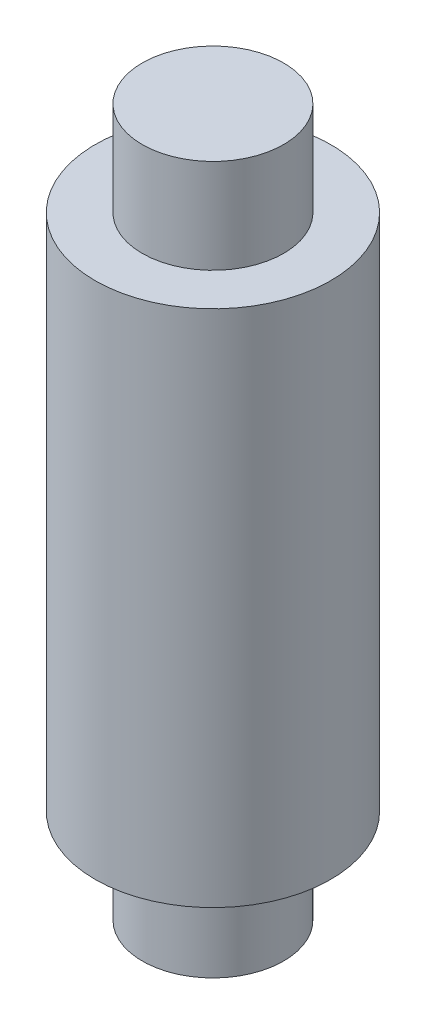
SolidWorks part; units mm, degrees
ref_plane "Спереди" through (0, 0, 0) normal (0, 0, 1) x (1, 0, 0)
ref_plane "Сверху" through (0, 0, 0) normal (0, 1, 0) x (1, 0, 0)
ref_plane "Справа" through (0, 0, 0) normal (1, 0, 0) x (0, 0, -1)
sketch "Эскиз1" plane through (0, 0, 0) normal (0, 1, 0) x (1, 0, 0)
  circle A0 centre (0, 0) radius 2.5
  dimension "D1" = 5
extrude "Бобышка-Вытянуть1" add sketch "Эскиз1" along normal blind 11
sketch "Эскиз2" plane through (0, 11, 0) normal (0, 1, 0) x (1, 0, 0)
  circle A0 centre (0, 0) radius 1.5
  dimension "D1" = 3
extrude "Бобышка-Вытянуть2" add sketch "Эскиз2" along normal blind 2
sketch "Эскиз4" plane through (0, 0, 0) normal (0, -1, 0) x (1, 0, 0)
  circle A0 centre (0, 0) radius 1.5
  circle A1 centre (0, 0) radius 1.5 construction
extrude "Бобышка-Вытянуть3" add sketch "Эскиз4" along normal blind 2
